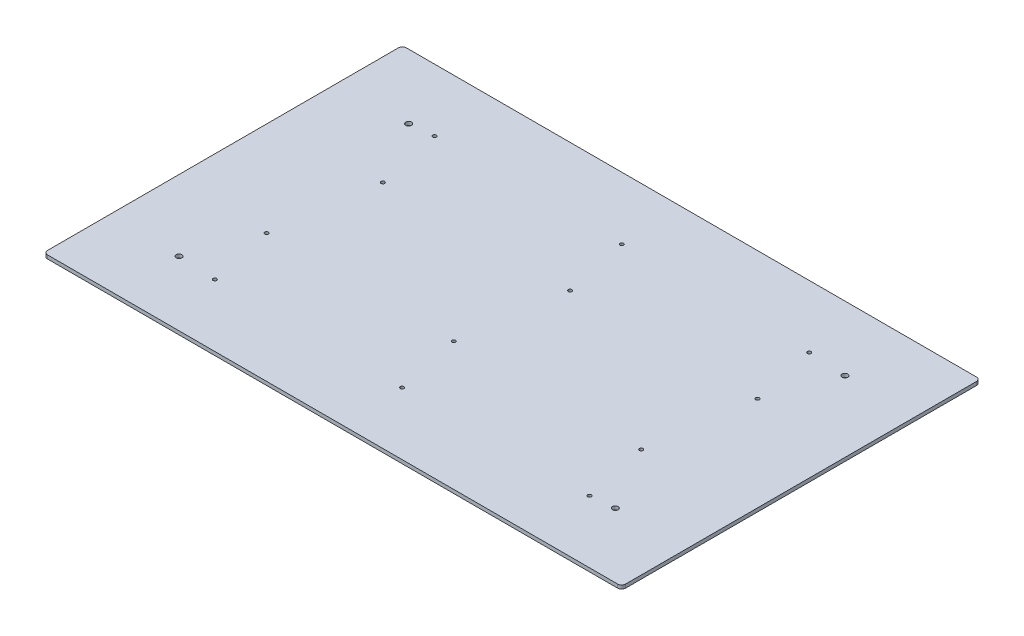
SolidWorks part; units mm, degrees
material "1060 Alloy"
ref_plane "Front" through (0, 0, 0) normal (0, 0, 1) x (1, 0, 0)
ref_plane "Top" through (0, 0, 0) normal (0, 1, 0) x (1, 0, 0)
ref_plane "Right" through (0, 0, 0) normal (1, 0, 0) x (0, 0, -1)
sketch "Sketch1" plane through (0, 0, 0) normal (0, 1, 0) x (1, 0, 0)
  line L1 (-184.15, -114.3) -> (184.15, -114.3)
  line L2 (-184.15, -114.3) -> (-184.15, 114.3)
  line L3 (-184.15, 114.3) -> (184.15, 114.3)
  line L4 (184.15, -114.3) -> (184.15, 114.3)
  line L5 (-184.15, -114.3) -> (184.15, 114.3) construction
  line L6 (-184.15, 114.3) -> (184.15, -114.3) construction
  point P0 (0, 0)
  dimension "D1" = 368.3
  dimension "D2" = 228.6
extrude "Boss-Extrude1" add sketch "Sketch1" along normal blind 2.286
hole_wizard "#6 Clearance Hole1" positions "Sketch2" profile "Sketch3" hole size "#6" standard "ANSI Inch" end condition through all
sketch "Sketch2" plane through (0, 0, 0) normal (0, -1, 0) x (-1, 0, 0)
  point P0 (-139.0015, 73.152)
  point P3 (139.0015, 73.152)
  point P6 (139.0015, -73.152)
  point P9 (-139.0015, -73.152)
sketch "Sketch3" plane through (139.0015, 0, -73.152) normal (1, 0, 0) x (0, 0, -1)
  line L0 (0, 0) -> (0, 2.286)
  line L1 (0, 2.286) -> (1.8288, 2.286)
  line L2 (1.8288, 2.286) -> (1.8288, 0)
  line L5 (1.8288, 0) -> (0, 0)
  line L11 (0, -6.35) -> (0, 107.95) construction
  dimension "Thru Hole Dia." = 3.6576
  dimension "Thru Hole Depth" = 2.286
hole_wizard "Tap Drill for #4-40 Tap1" positions "Sketch4" profile "Sketch5" hole size "#4-40" standard "ANSI Inch" end condition through all
sketch "Sketch4" plane through (0, 0, 0) normal (0, -1, 0) x (-1, 0, 0)
  point P0 (-114.8474, 74.5473)
  point P3 (-123.9126, 32.5137)
  point P6 (4.5326, 74.5473)
  point P9 (-4.5326, 32.5137)
  point P12 (123.9126, 74.5473)
  point P15 (114.8474, 32.5137)
  point P18 (123.9126, -32.5137)
  point P21 (114.8474, -74.5473)
  point P24 (4.5326, -32.5137)
  point P27 (-4.5326, -74.5473)
  point P30 (-114.8474, -32.5137)
  point P33 (-123.9126, -74.5473)
sketch "Sketch5" plane through (114.8474, 0, -74.5473) normal (1, 0, 0) x (0, 0, -1)
  line L0 (0, 0) -> (0, 2.286)
  line L1 (0, 2.286) -> (1.1303, 2.286)
  line L2 (1.1303, 2.286) -> (1.1303, 0)
  line L5 (1.1303, 0) -> (0, 0)
  line L11 (0, -6.35) -> (0, 107.95) construction
  dimension "Thru Hole Dia." = 2.2606
  dimension "Thru Hole Depth" = 2.286
fillet "Fillet1" radius 2.54 4 edges at (184.15, 1.143, -114.3) (-184.15, 1.143, -114.3) (-184.15, 1.143, 114.3) (184.15, 1.143, 114.3)
